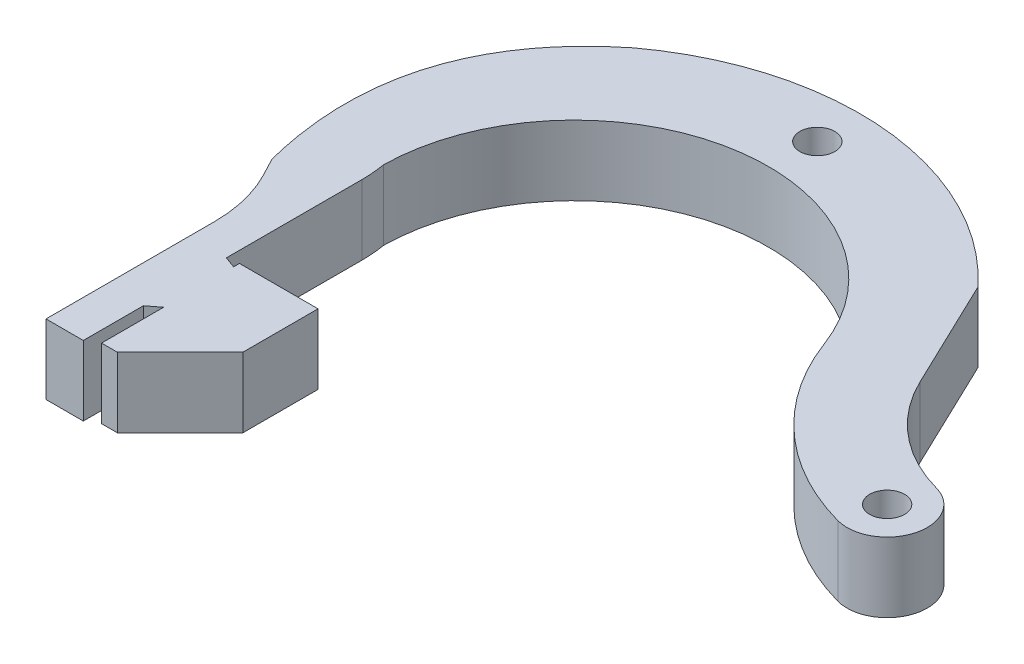
SolidWorks part; units mm, degrees
ref_plane "Front Plane" through (0, 0, 0) normal (0, 0, 1) x (1, 0, 0)
ref_plane "Top Plane" through (0, 0, 0) normal (0, 1, 0) x (1, 0, 0)
ref_plane "Right Plane" through (0, 0, 0) normal (1, 0, 0) x (0, 0, -1)
sketch "Sketch1" plane through (0, 0, 0) normal (0, 1, 0) x (1, 0, 0)
  line L0 (-90.9036, 63.2256) -> (22.3091, 63.2256) construction
  line L1 (-15, 0) -> (15, 0) construction
  line L2 (-26.25, 10.75) -> (-15, 10.75)
  line L3 (-15, 10.75) -> (-15, 0)
  line L4 (-15, 0) -> (-23.9848, -9)
  line L5 (-23.9848, -9) -> (-26.25, -9)
  line L6 (-26.25, -9) -> (-26.25, -0.1143)
  line L7 (-26.25, 9.912) -> (-29.4384, 11.0733)
  line L8 (-29.4384, 11.0733) -> (-29.4384, -2.5551)
  line L9 (-29.4384, -2.5551) -> (-26.25, -0.1143)
  line L10 (-26.25, 10.75) -> (-26.25, 9.912)
  point P6 (0, 0)
  dimension "D1" = 30
  dimension "D2" = 10.75
  dimension "D3" = 11.25
  dimension "D4" = 19.75
  dimension "D5" = 12.7171
sketch "Sketch2" plane through (0, 0, 0) normal (0, 1, 0) x (1, 0, 0)
  line L0 (-33.2263, -9.9819) -> (-27.8836, -9.9819)
  line L1 (-27.8836, -9.9819) -> (-27.8836, 29.9253)
  line L2 (-15, 0) -> (15, 0) construction
  line L3 (-33.2263, -9.9819) -> (-33.2263, 14.1708)
  line L4 (-35.5403, 23.5091) -> (-36.8668, 26.0215)
  line L5 (37.1739, 44.781) -> (29.5445, 60.7106)
  circle A0 centre (0, 67.25) radius 2.5
  arc A1 (-33.2263, 14.1708) -> (-35.5403, 23.5091) centre (-53.2263, 14.1708) ccw
  arc A2 (-27.8836, 29.9253) -> (-28.1745, 33.3237) centre (-47.8836, 29.9253) ccw
  circle A3 centre (50, 27.25) radius 2.5
  arc A4 (51.5214, 32.7951) -> (48.4786, 21.7049) centre (50, 27.25) cw
  arc A5 (48.4786, 21.7049) -> (25.615, 42.6054) centre (57.4783, 54.5057) cw
  arc A6 (51.5214, 32.7951) -> (37.1739, 44.781) centre (57.4783, 54.5057) cw
  arc A7 (25.615, 42.6054) -> (-28.1745, 33.3237) centre (-0.4038, 32.888) ccw
  arc A8 (29.5445, 60.7106) -> (-24.8019, 65.6862) centre (-0.4038, 32.888) ccw
  spline S1 degree 2 poles (-36.8668, 26.0215) (-43.2248, 50.9576) (-24.8019, 65.6862) knots 0 0 0 1 1 1
  point P8 (0, 0)
  point P13 (0, 0)
  dimension "D2" = 20
  dimension "D3" = 20
  dimension "D4" = 5.75
  dimension "D5" = 34.0131
  dimension "D6" = 50
  dimension "D8" = 5
  dimension "D9" = 79.2126
  dimension "D10" = 27.7742
  dimension "D15" = 5
  dimension "D7" = 27.25
  dimension "D11" = 32.888
  dimension "D12" = 17.6624
  dimension "D13" = 60.7106
  dimension "D14" = 67.25
extrude "Boss-Extrude1" add sketch "Sketch2" along normal blind 10
extrude "Boss-Extrude2" add sketch "Sketch1" along normal blind 10
